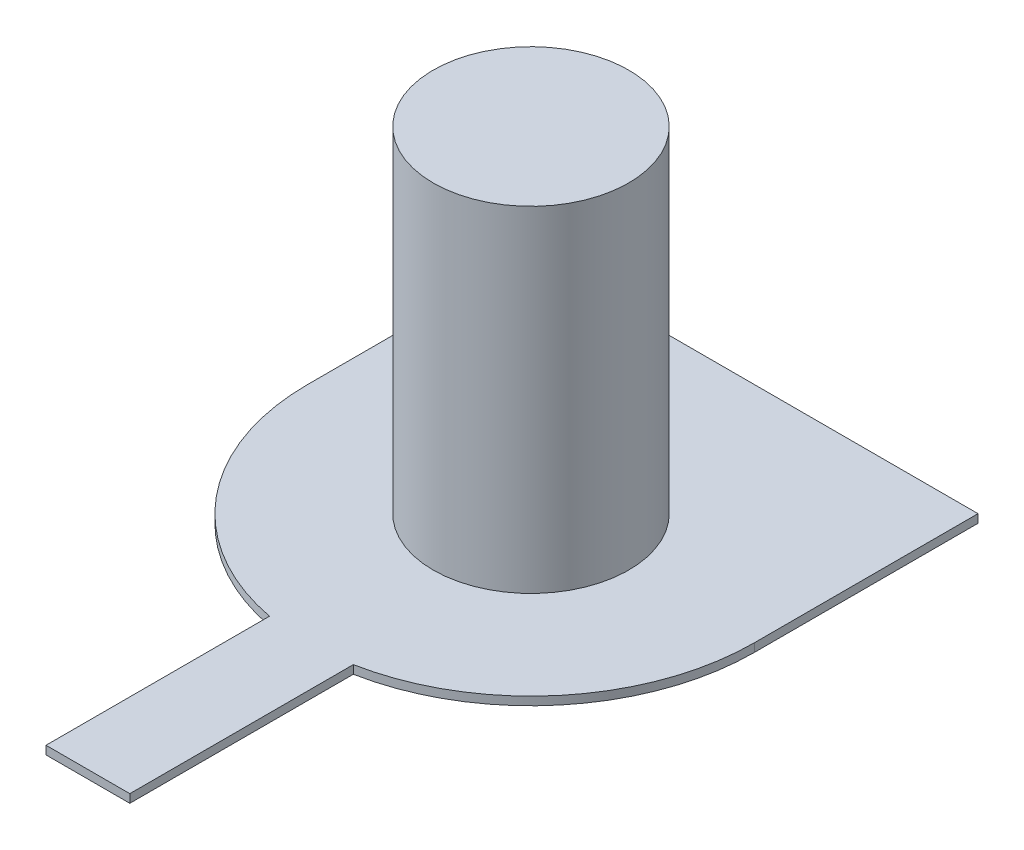
SolidWorks part; units mm, degrees
ref_plane "前视基准面" through (0, 0, 0) normal (0, 0, 1) x (1, 0, 0)
ref_plane "上视基准面" through (0, 0, 0) normal (0, 1, 0) x (1, 0, 0)
ref_plane "右视基准面" through (0, 0, 0) normal (1, 0, 0) x (0, 0, -1)
other "Configuration Table"
sketch "草图1" plane through (0, 0, 0) normal (0, 1, 0) x (1, 0, 0)
  line L0 (-8, 0) -> (-8, 8)
  line L1 (-8, 8) -> (8, 8)
  line L2 (8, 8) -> (8, 0)
  line L3 (0, 0) -> (0, -15.8581) construction
  line L5 (-1.5, -7.8581) -> (-1.5, -15.8581)
  line L6 (-1.5, -15.8581) -> (1.5, -15.8581)
  line L7 (1.5, -7.8581) -> (1.5, -15.8581)
  arc A0 (-8, 0) -> (-1.5, -7.8581) centre (0, 0) ccw
  arc A1 (1.5, -7.8581) -> (8, 0) centre (0, 0) ccw
  dimension "D1" = 8
  dimension "D2" = 3
  dimension "D3" = 8
extrude "凸台-拉伸1" add sketch "草图1" along normal blind 0.3
sketch "草图2" plane through (0, 0.3, 0) normal (0, 1, 0) x (1, 0, 0)
  circle A0 centre (0, 0) radius 3.5
  dimension "D1" = 7
extrude "凸台-拉伸2" add sketch "草图2" along normal blind 12
